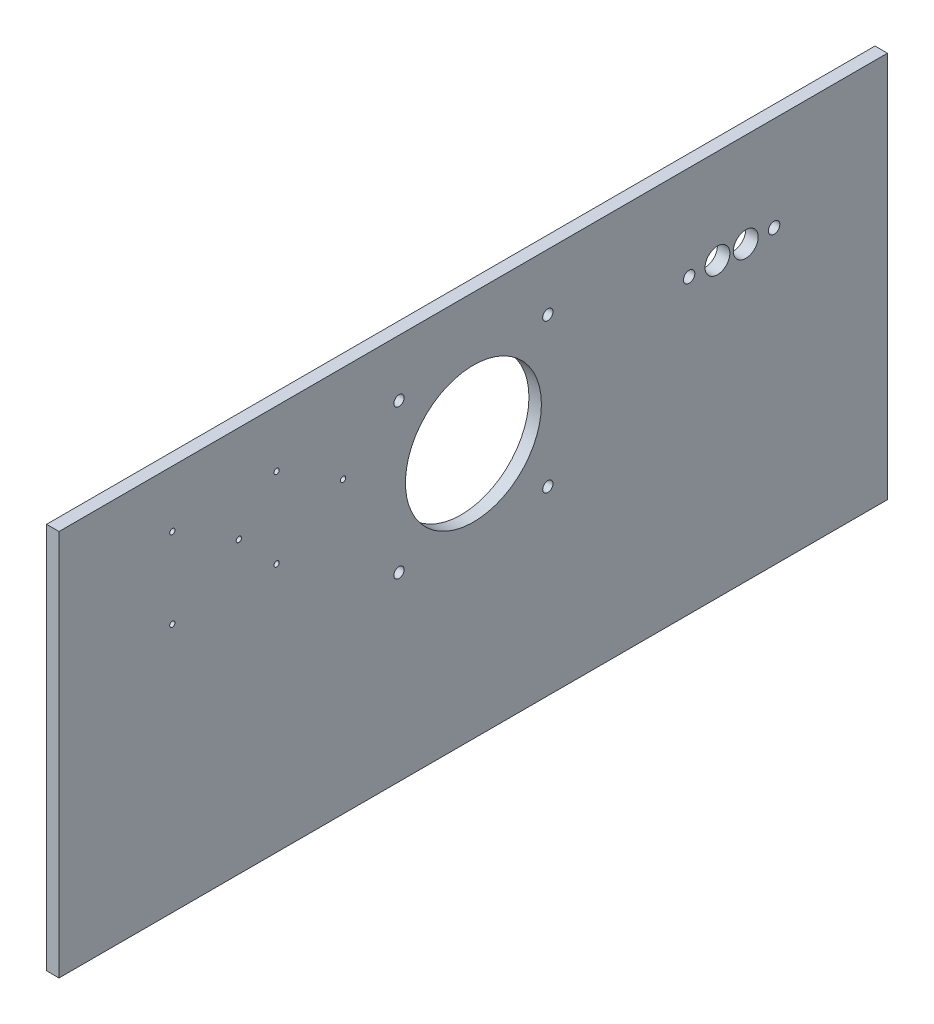
SolidWorks part; units mm, degrees
ref_plane "Front Plane" through (0, 0, 0) normal (0, 0, 1) x (1, 0, 0)
ref_plane "Top Plane" through (0, 0, 0) normal (0, 1, 0) x (1, 0, 0)
ref_plane "Right Plane" through (0, 0, 0) normal (1, 0, 0) x (0, 0, -1)
sketch "Sketch1" plane through (0, 0, 0) normal (1, 0, 0) x (0, 0, -1)
  line L1 (0, 0) -> (278.511, 0)
  line L2 (0, 0) -> (0, 129.9972)
  line L3 (0, 129.9972) -> (278.511, 129.9972)
  line L4 (278.511, 0) -> (278.511, 129.9972)
  dimension "D1" = 129.9972
  dimension "D2" = 278.511
extrude "Boss-Extrude1" add sketch "Sketch1" along normal blind 4.191
sketch "Sketch17" plane through (4.191, 0, 0) normal (1, 0, 0) x (0, 0, -1)
  line L0 (278.511, 129.9972) -> (0, 129.9972) construction
  line L1 (0, 129.9972) -> (0, 0) construction
  point P0 (114.3, 110.9472)
  point P1 (114.3, 60.9092)
  point P2 (164.338, 110.9472)
  point P3 (164.338, 60.9092)
  point P8 (38.1, 110.9472)
  point P9 (38.1, 83.9724)
  point P10 (60.452, 97.4598)
  point P11 (73.152, 110.9472)
  point P12 (95.504, 97.4598)
  point P13 (73.152, 83.9724)
  dimension "D1" = 50.038
  dimension "D2" = 50.038
  dimension "D3" = 19.05
  dimension "D4" = 114.3
  dimension "D5" = 26.9748
  dimension "D6" = 13.4874
  dimension "D7" = 22.352
  dimension "D8" = 22.352
  dimension "D9" = 12.7
  dimension "D10" = 19.05
  dimension "D11" = 38.1
hole_wizard "#2-56 Tapped Hole2" positions "Sketch21" profile "Sketch20" tap size "#2-56" standard "ANSI Inch" end condition through all
sketch "Sketch21" plane through (4.191, 0, 0) normal (1, 0, 0) x (0, 0, -1)
  point P0 (38.1, 83.9724)
  point P3 (38.1, 110.9472)
  point P6 (60.452, 97.4598)
  point P9 (73.152, 110.9472)
  point P12 (73.152, 83.9724)
  point P15 (95.504, 97.4598)
sketch "Sketch20" plane through (4.191, 83.9724, -38.1) normal (0, 1, 0) x (0, 0, -1)
  line L0 (0, 0) -> (0, 4.191)
  line L1 (0, 4.191) -> (0.889, 4.191)
  line L2 (0.889, 4.191) -> (0.889, 0)
  line L5 (0.889, 0) -> (0, 0)
  line L11 (0, -6.35) -> (0, 107.95) construction
  dimension "Thru Tap Drill Dia." = 1.778
  dimension "Thru Tap Drill Depth" = 4.191
cosmetic thread "Hole Thread10" parameters "D2"=2.1844
cosmetic thread "Hole Thread11" parameters "D2"=2.1844
cosmetic thread "Hole Thread12" parameters "D2"=2.1844
cosmetic thread "Hole Thread13" parameters "D2"=2.1844
cosmetic thread "Hole Thread14" parameters "D2"=2.1844
cosmetic thread "Hole Thread15" parameters "D2"=2.1844
hole_wizard "#8-32 Tapped Hole1" positions "Sketch23" profile "Sketch22" tap size "#8-32" standard "ANSI Inch" end condition through all
sketch "Sketch23" plane through (4.191, 0, 0) normal (1, 0, 0) x (0, 0, -1)
  point P0 (114.3, 60.9092)
  point P3 (114.3, 110.9472)
  point P6 (164.338, 110.9472)
  point P9 (164.338, 60.9092)
sketch "Sketch22" plane through (4.191, 60.9092, -114.3) normal (0, 1, 0) x (0, 0, -1)
  line L0 (0, 0) -> (0, 4.191)
  line L1 (0, 4.191) -> (1.7272, 4.191)
  line L2 (1.7272, 4.191) -> (1.7272, 0)
  line L5 (1.7272, 0) -> (0, 0)
  line L11 (0, -6.35) -> (0, 107.95) construction
  dimension "Thru Tap Drill Dia." = 3.4544
  dimension "Thru Tap Drill Depth" = 4.191
cosmetic thread "Hole Thread16" parameters "D2"=4.1656
cosmetic thread "Hole Thread17" parameters "D2"=4.1656
cosmetic thread "Hole Thread18" parameters "D2"=4.1656
cosmetic thread "Hole Thread19" parameters "D2"=4.1656
sketch "Sketch25" plane through (4.191, 0, 0) normal (1, 0, 0) x (0, 0, -1)
  circle A0 centre (139.319, 85.9282) radius 22.86
  dimension "D3" = 45.72
  dimension "D1" = 25.019
  dimension "D2" = 25.019
extrude "Cut-Extrude1" cut sketch "Sketch25" against normal up to next
sketch "Sketch27" plane through (4.191, 0, 0) normal (1, 0, 0) x (0, 0, -1)
  line L0 (278.511, 0) -> (278.511, 129.9972) construction
  circle A0 centre (221.361, 98.2472) radius 4.1656
  circle A1 centre (211.836, 98.2472) radius 1.905
  circle A2 centre (230.886, 98.2472) radius 4.1656
  circle A3 centre (240.411, 98.2472) radius 1.905
  dimension "D1" = 3.81
  dimension "D2" = 3.81
  dimension "D3" = 8.3312
  dimension "D4" = 8.3312
  dimension "D5" = 9.525
  dimension "D6" = 9.525
  dimension "D7" = 9.525
  dimension "D8" = 12.7
  dimension "D9" = 38.1
extrude "Cut-Extrude2" cut sketch "Sketch27" against normal up to next
